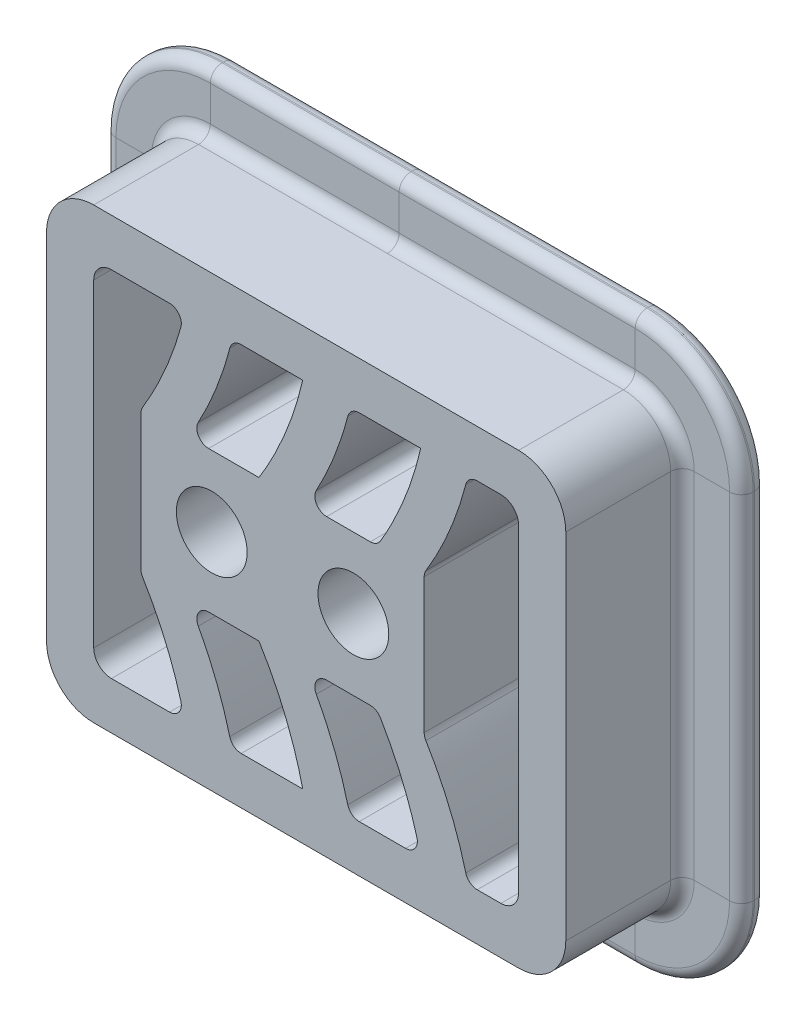
SolidWorks part; units mm, degrees
ref_plane "Front Plane" through (0, 0, 0) normal (0, 0, 1) x (1, 0, 0)
ref_plane "Top Plane" through (0, 0, 0) normal (0, 1, 0) x (1, 0, 0)
ref_plane "Right Plane" through (0, 0, 0) normal (1, 0, 0) x (0, 0, -1)
sketch "Sketch1" plane through (0, 0, 0) normal (0, 0, 1) x (1, 0, 0)
  line L0 (-3, 0) -> (3, 0) construction
  line L1 (9.9, 0) -> (-9.9, 0) construction
  line L2 (-6, -3) -> (6, 3) construction
  line L3 (-6, 3) -> (6, 3)
  line L4 (-6, 3) -> (-6, -3)
  line L5 (-6, -3) -> (6, -3)
  line L6 (6, 3) -> (6, -3)
  line L7 (-6, 3) -> (6, -3) construction
  circle A0 centre (-3, 0) radius 1.5
  circle A1 centre (3, 0) radius 1.5
  point P5 (0, 0)
  point P12 (0, 0)
  dimension "D2" = 3
  dimension "D1" = 6
  dimension "D3" = 3
  dimension "D4" = 3
extrude "Boss-Extrude1" add sketch "Sketch1" along normal mid plane 6
sketch "Sketch2" plane through (0, 0, 0) normal (0, 0, 1) x (1, 0, 0)
  line L1 (-8, -7.5) -> (10, -7.5)
  line L2 (-8, -7.5) -> (-8, 7.5)
  line L3 (-8, 7.5) -> (10, 7.5)
  line L4 (10, -7.5) -> (10, 7.5)
  line L8 (-10, -9.5) -> (-10, 9.5)
  line L9 (-10, 9.5) -> (12, 9.5)
  line L10 (12, -9.5) -> (12, 9.5)
  line L11 (-10, -9.5) -> (12, -9.5)
  point P0 (0, 0)
  dimension "D1" = 18
  dimension "D2" = 15
  dimension "D3" = 2
  dimension "D4" = 10
  dimension "D5" = 7.5
extrude "Boss-Extrude2" add sketch "Sketch2" along normal mid plane 6 separate body
sketch "Sketch3" plane through (0, 0, 0) normal (0, 0, 1) x (1, 0, 0)
  line L0 (10, 7.5) -> (-8, 7.5) construction
  line L1 (6, 3) -> (-6, 3) construction
  line L2 (-6, 3) -> (-4, 3)
  line L3 (-4.145, 7.5) -> (-2.145, 7.5)
  line L4 (0.855, 7.5) -> (2.855, 7.5)
  line L5 (-1, 3) -> (1, 3)
  line L6 (5.855, 7.5) -> (7.855, 7.5)
  line L7 (4, 3) -> (6, 3)
  line L8 (3.3, 0) -> (-3.3, 0) construction
  line L9 (4, -3) -> (6, -3)
  line L10 (5.855, -7.5) -> (7.855, -7.5)
  line L11 (-1, -3) -> (1, -3)
  line L12 (0.855, -7.5) -> (2.855, -7.5)
  line L13 (-6, -3) -> (-4, -3)
  line L14 (-4.145, -7.5) -> (-2.145, -7.5)
  spline S0 degree 2 poles (-4.145, 7.5) (-4.7016, 5.105) (-6, 3) knots 0 0 0 1 1 1
  spline S1 degree 2 poles (-2.145, 7.5) (-2.7016, 5.105) (-4, 3) knots 0 0 0 1 1 1
  spline S2 degree 2 poles (2.855, 7.5) (2.2984, 5.105) (1, 3) knots 0 0 0 1 1 1
  spline S3 degree 2 poles (0.855, 7.5) (0.2984, 5.105) (-1, 3) knots 0 0 0 1 1 1
  spline S4 degree 2 poles (7.855, 7.5) (7.2984, 5.105) (6, 3) knots 0 0 0 1 1 1
  spline S5 degree 2 poles (5.855, 7.5) (5.2984, 5.105) (4, 3) knots 0 0 0 1 1 1
  spline S6 degree 2 poles (5.855, -7.5) (5.2984, -5.105) (4, -3) knots 0 0 0 1 1 1
  spline S7 degree 2 poles (7.855, -7.5) (7.2984, -5.105) (6, -3) knots 0 0 0 1 1 1
  spline S8 degree 2 poles (0.855, -7.5) (0.2984, -5.105) (-1, -3) knots 0 0 0 1 1 1
  spline S9 degree 2 poles (2.855, -7.5) (2.2984, -5.105) (1, -3) knots 0 0 0 1 1 1
  spline S10 degree 2 poles (-4.145, -7.5) (-4.7016, -5.105) (-6, -3) knots 0 0 0 1 1 1
  spline S11 degree 2 poles (-2.145, -7.5) (-2.7016, -5.105) (-4, -3) knots 0 0 0 1 1 1
  dimension "D1" = 3
  dimension "D2" = 2
extrude "Boss-Extrude3" add sketch "Sketch3" along normal mid plane 6
sketch "Sketch5" plane through (0, 0, 0) normal (1, 0, 0) x (0, 0, -1)
  line L0 (-1.9402, 9.5) -> (1.9402, 9.5) construction
  line L1 (0, 10.45) -> (0, -10.45) construction
  line L2 (-3, 9.5) -> (3, 9.5) construction
  line L7 (3, 12) -> (3, 9.5)
  line L8 (1.9402, 12) -> (3, 12)
  line L9 (1.9402, 9.5) -> (1.9402, 12)
  line L10 (3, 9.5) -> (1.9402, 9.5)
  point P2 (0, 9.5)
  point P8 (0, 0)
  point P9 (0, 0)
  dimension "D3" = 2.5
fillet "Fillet3" radius 2 4 edges at (12, 9.5, 0) (12, -9.5, 0) (-10, -9.5, 0) (-10, 9.5, 0)
sketch "Sketch6" plane through (0, 0, 0) normal (0, 0, 1) x (1, 0, 0)
  line L0 (12, -7.5) -> (12, 7.5) construction
  line L1 (-8, -9.5) -> (10, -9.5) construction
  line L2 (-10, 7.5) -> (-10, -7.5) construction
  line L3 (10, 9.5) -> (-8, 9.5) construction
  line L4 (12, -7.5) -> (12, 7.5)
  line L5 (-8, -9.5) -> (10, -9.5)
  line L6 (-10, 7.5) -> (-10, -7.5)
  line L7 (10, 9.5) -> (-8, 9.5)
  arc A0 (12, 7.5) -> (10, 9.5) centre (10, 7.5) ccw construction
  arc A1 (10, -9.5) -> (12, -7.5) centre (10, -7.5) ccw construction
  arc A2 (-10, -7.5) -> (-8, -9.5) centre (-8, -7.5) ccw construction
  arc A3 (-8, 9.5) -> (-10, 7.5) centre (-8, 7.5) ccw construction
  arc A4 (12, 7.5) -> (10, 9.5) centre (10, 7.5) ccw
  arc A5 (10, -9.5) -> (12, -7.5) centre (10, -7.5) ccw
  arc A6 (-10, -7.5) -> (-8, -9.5) centre (-8, -7.5) ccw
  arc A7 (-8, 9.5) -> (-10, 7.5) centre (-8, 7.5) ccw
sweep "Sweep1" add profiles "Sketch5" path "Sketch6"
fillet "Fillet4" radius 0.5 27 edges at (-9.4142, 8.9142, -1.9402) (-10, 0, -1.9402) (-9.4142, -8.9142, -1.9402) (1, -9.5, -1.9402) (11.4142, -8.9142, -1.9402) (12, 0, -1.9402) (11.4142, 8.9142, -1.9402) (5, 9.5, -1.9402) (-4, 9.5, -1.9402) (5, 12, -1.9402) (5, 12, -3) (-4, 12, -1.9402) (-4, 12, -3) (-11.182, 10.682, -1.9402) (-11.182, 10.682, -3) (-12.5, 0, -1.9402) (-12.5, 0, -3) (-11.182, -10.682, -1.9402) (-11.182, -10.682, -3) (1, -12, -1.9402) (1, -12, -3) (13.182, -10.682, -1.9402) (13.182, -10.682, -3) (14.5, 0, -1.9402) (14.5, 0, -3) (13.182, 10.682, -1.9402) (13.182, 10.682, -3)
fillet "Fillet5" radius 0.75 4 edges at (10, 7.5, 0) (10, -7.5, 0) (-8, -7.5, 0) (-8, 7.5, 0)
fillet "Fillet6" radius 0.5 19 edges at (-4.145, -7.5, 0) (-4.145, 7.5, 0) (-6, -3, 0) (-6, 3, 0) (4, 3, 0) (1, 3, 0) (-4, 3, 0) (-2.145, 7.5, 0) (2.855, 7.5, 0) (7.855, 7.5, 0) (6, 3, 0) (6, -3, 0) (7.855, -7.5, 0) (4, -3, 0) (5.855, -7.5, 0) (2.855, -7.5, 0) (1, -3, 0) (-4, -3, 0) (-2.145, -7.5, 0)
